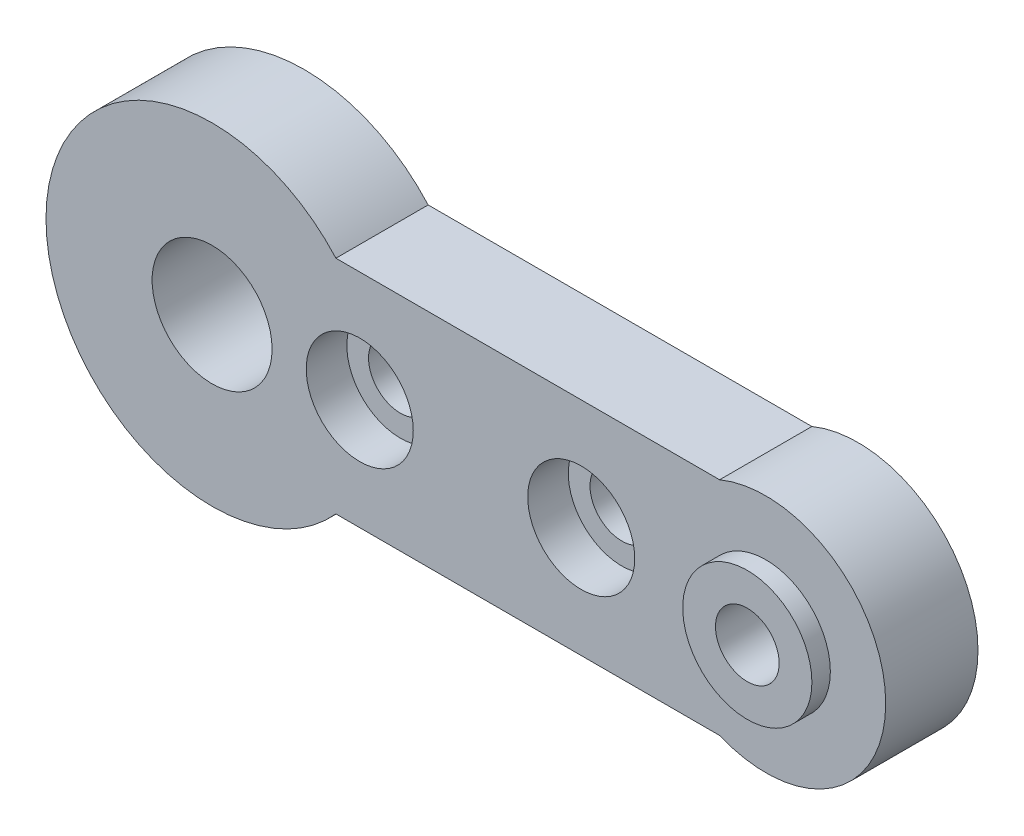
SolidWorks part; units mm, degrees
ref_plane "Front Plane" through (0, 0, 0) normal (0, 0, 1) x (1, 0, 0)
ref_plane "Top Plane" through (0, 0, 0) normal (0, 1, 0) x (1, 0, 0)
ref_plane "Right Plane" through (0, 0, 0) normal (1, 0, 0) x (0, 0, -1)
sketch "Sketch1" plane through (0, 0, 0) normal (0, 0, 1) x (1, 0, 0)
  line L0 (0, -6) -> (30, -6)
  line L1 (30, -6) -> (30, 6)
  line L2 (30, 6) -> (0, 6)
  line L3 (0, 6) -> (0, -6)
extrude "Boss-Extrude1" add sketch "Sketch1" along normal blind 5 from offset 9
sketch "Sketch2" plane through (0, 0, 0) normal (0, 0, 1) x (1, 0, 0)
  circle A0 centre (0, 0) radius 9
extrude "Boss-Extrude2" add sketch "Sketch2" along normal blind 5 from offset 9
sketch "Sketch3" plane through (0, 0, 0) normal (0, 0, 1) x (1, 0, 0)
  circle A0 centre (30, 0) radius 6.5
extrude "Boss-Extrude3" add sketch "Sketch3" along normal blind 5 from offset 9
sketch "Sketch4" plane through (0, 0, 0) normal (0, 0, 1) x (1, 0, 0)
  circle A0 centre (0, 0) radius 3.25
extrude "Cut-Extrude1" cut sketch "Sketch4" against normal through all and the other way through all
sketch "Sketch5" plane through (0, 0, 0) normal (0, 0, 1) x (1, 0, 0)
  circle A0 centre (8, 0) radius 1.725
  circle A1 centre (20, 0) radius 1.725
  circle A2 centre (30, 0) radius 1.725
extrude "Cut-Extrude2" cut sketch "Sketch5" against normal through all and the other way through all
sketch "Sketch6" plane through (0, 0, 0) normal (0, 0, 1) x (1, 0, 0)
  circle A0 centre (8, 0) radius 2.9
extrude "Cut-Extrude3" cut sketch "Sketch6" along normal blind 2.2 from offset 6.2
sketch "Sketch7" plane through (0, 0, 0) normal (0, 0, 1) x (1, 0, 0)
  circle A0 centre (20, 0) radius 2.9
extrude "Cut-Extrude4" cut sketch "Sketch7" along normal blind 2.2 from offset 6.2
sketch "Sketch8" plane through (0, 0, 0) normal (0, 0, 1) x (1, 0, 0)
  circle A0 centre (30, 0) radius 2.9
extrude "Cut-Extrude5" cut sketch "Sketch8" along normal blind 2.2 from offset 9
sketch "Sketch9" plane through (0, 0, 0) normal (0, 0, 1) x (1, 0, 0)
  circle A0 centre (30, 0) radius 3.5
extrude "Boss-Extrude4" add sketch "Sketch9" along normal blind 1 from offset 4
sketch "Sketch10" plane through (0, 0, 0) normal (0, 0, 1) x (1, 0, 0)
  circle A0 centre (30, 0) radius 1.725
extrude "Cut-Extrude6" cut sketch "Sketch10" against normal through all and the other way through all
